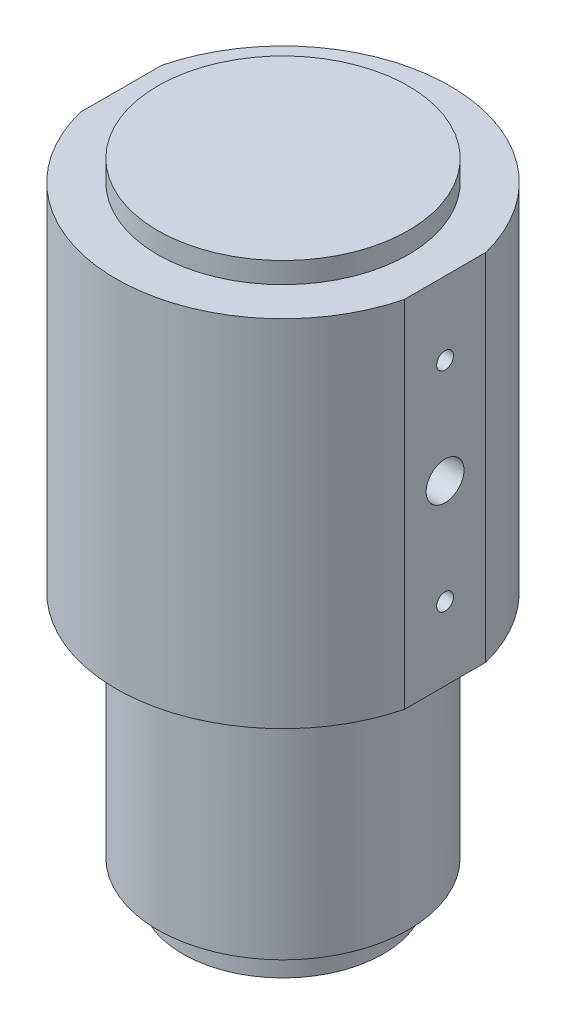
SolidWorks part; units mm, degrees
ref_plane "Front Plane" through (0, 0, 0) normal (0, 0, 1) x (1, 0, 0)
ref_plane "Top Plane" through (0, 0, 0) normal (0, 1, 0) x (1, 0, 0)
ref_plane "Right Plane" through (0, 0, 0) normal (1, 0, 0) x (0, 0, -1)
sketch "Sketch1" plane through (0, 0, 0) normal (0, 1, 0) x (1, 0, 0)
  circle A0 centre (0, 0) radius 50.8
  dimension "D1" = 101.6
extrude "Boss-Extrude1" add sketch "Sketch1" along normal blind 107.95
sketch "Sketch2" plane through (0, 107.95, 0) normal (0, 1, 0) x (1, 0, 0)
  circle A0 centre (0, 0) radius 38.1
  dimension "D1" = 76.2
extrude "Boss-Extrude2" add sketch "Sketch2" along normal blind 6.35 contours A0
sketch "Sketch3" plane through (0, 0, 0) normal (0, -1, 0) x (1, 0, 0)
  circle A0 centre (0, 0) radius 38.1
  dimension "D1" = 76.2
extrude "Boss-Extrude3" add sketch "Sketch3" along normal blind 69.85
sketch "Sketch4" plane through (0, -69.85, 0) normal (0, -1, 0) x (1, 0, 0)
  circle A0 centre (0, 0) radius 30.48
  dimension "D1" = 60.96
extrude "Boss-Extrude4" add sketch "Sketch4" along normal blind 10.16
sketch "Sketch5" plane through (0, -80.01, 0) normal (0, -1, 0) x (1, 0, 0)
  circle A0 centre (0, 0) radius 15.875
  dimension "D1" = 31.75
extrude "Cut-Extrude1" cut sketch "Sketch5" against normal blind 82.55 contours A0
sketch "Sketch7" plane through (0, 107.95, 0) normal (0, 1, 0) x (1, 0, 0)
  line L0 (0, 0) -> (0, 73.9004) construction
  line L1 (-49.276, 63.5) -> (49.276, 63.5)
  line L2 (-49.276, 63.5) -> (-49.276, -63.5)
  line L3 (-49.276, -63.5) -> (49.276, -63.5)
  line L4 (49.276, 63.5) -> (49.276, -63.5)
  line L5 (0, 0) -> (75.605, 0) construction
  dimension "D1" = 98.552
  dimension "D2" = 49.276
  dimension "D3" = 63.5
  dimension "D4" = 127
extrude "Cut-Extrude2" cut sketch "Sketch7" against normal blind 107.95 flip side to cut
hole_wizard "1/2-20 Tapped Hole1" positions "Sketch9" profile "Sketch8" tap size "1/2-20" standard "ANSI Inch" end condition through all
sketch "Sketch9" plane through (-49.276, 0, 0) normal (-1, 0, 0) x (0, 0, 1)
  line L1 (0, 114.3) -> (0, -80.01) construction
  line L2 (38.1, 114.3) -> (-38.1, 114.3) construction
  line L3 (-30.48, -80.01) -> (30.48, -80.01) construction
  line L4 (38.1, 107.95) -> (-38.1, 107.95) construction
  point P12 (0, 53.975)
  dimension "D1" = 53.975
sketch "Sketch8" plane through (-49.276, 53.975, 0) normal (0, 1, 0) x (0, 0, 1)
  line L0 (0, 0) -> (0, 98.552)
  line L1 (0, 98.552) -> (5.7544, 98.552)
  line L2 (5.7544, 98.552) -> (5.7544, 0)
  line L5 (5.7544, 0) -> (0, 0)
  line L11 (0, -6.35) -> (0, 107.95) construction
  dimension "Thru Tap Drill Dia." = 11.5087
  dimension "Thru Tap Drill Depth" = 98.552
cosmetic thread "Hole Thread1" parameters "D2"=12.7
hole_wizard "1/4-20 Tapped Hole1" positions "Sketch11" profile "Sketch10" tap size "1/4-20" standard "ANSI Inch" end condition through all
sketch "Sketch11" plane through (-49.276, 0, 0) normal (-1, 0, 0) x (0, 0, 1)
  line L0 (0, 107.95) -> (0, 0) construction
  line L1 (-12.3497, 107.95) -> (12.3497, 107.95) construction
  circle A0 centre (0, 53.975) radius 5.7544 construction
  point P7 (0, 85.725)
  point P9 (0, 22.225)
  dimension "D1" = 31.75
  dimension "D2" = 31.75
sketch "Sketch10" plane through (-49.276, 85.725, 0) normal (0, 1, 0) x (0, 0, 1)
  line L0 (0, 0) -> (0, 98.552)
  line L1 (0, 98.552) -> (2.5527, 98.552)
  line L2 (2.5527, 98.552) -> (2.5527, 0)
  line L5 (2.5527, 0) -> (0, 0)
  line L11 (0, -6.35) -> (0, 107.95) construction
  dimension "Thru Tap Drill Dia." = 5.1054
  dimension "Thru Tap Drill Depth" = 98.552
cosmetic thread "Hole Thread2" parameters "D2"=6.35
cosmetic thread "Hole Thread3" parameters "D2"=6.35
equation "\"D2@Sketch7\"=\"D1@Sketch7\"/2"
equation "\"D3@Sketch7\"=\"D4@Sketch7\"/2"
